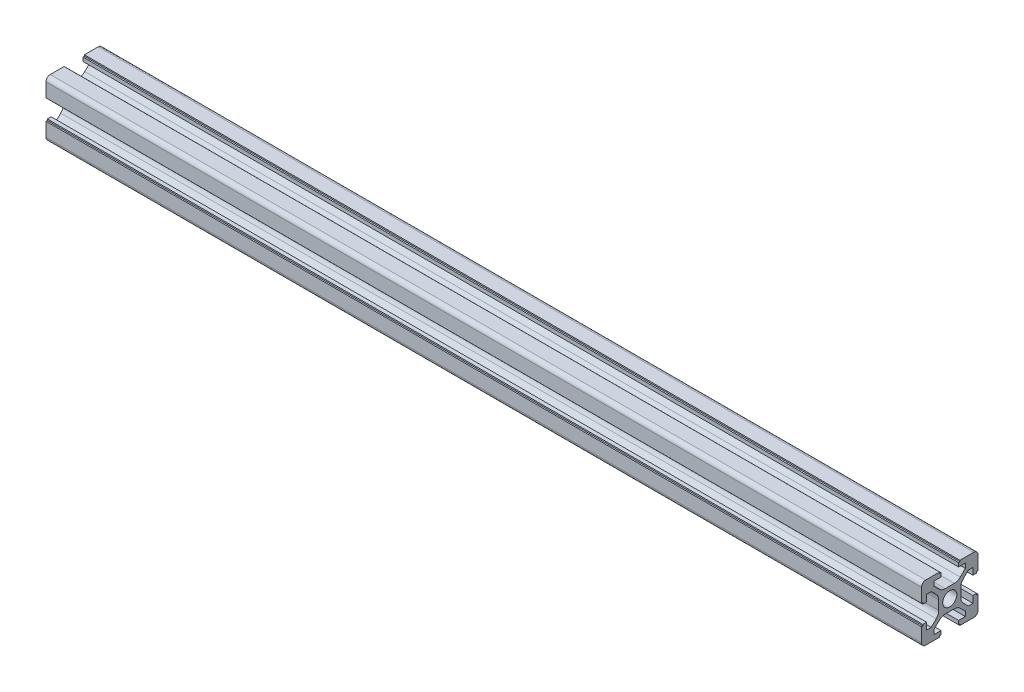
SolidWorks part; units mm, degrees
ref_plane "前视基准面" through (0, 0, 0) normal (0, 0, 1) x (1, 0, 0)
ref_plane "上视基准面" through (0, 0, 0) normal (0, 1, 0) x (1, 0, 0)
ref_plane "右视基准面" through (0, 0, 0) normal (1, 0, 0) x (0, 0, -1)
sketch "草图1" plane through (0, 0, 0) normal (1, 0, 0) x (0, 0, -1)
  line L0 (0, 0) -> (-10, 0) construction
  line L1 (0, 0) -> (0, 10) construction
  line L2 (0, 0) -> (-10, 10) construction
  line L3 (-10, 10) -> (-10, 3.6)
  line L4 (-10, 3.6) -> (-9.531, 3.6)
  line L5 (-9.531, 3.6) -> (-9.531, 3.1)
  line L6 (-9.531, 3.1) -> (-8.2, 3.1)
  line L7 (-8.2, 3.1) -> (-8.2, 5.5)
  line L8 (-8.2, 5.5) -> (-6.5607, 5.5)
  line L9 (-6.5607, 5.5) -> (-3.9, 2.8393)
  line L10 (-3.9, 2.8393) -> (-3.9, 0)
  line L11 (-3.6, 9.531) -> (-3.1, 9.531)
  line L12 (-2.8393, 3.9) -> (0, 3.9)
  line L13 (-5.5, 6.5607) -> (-2.8393, 3.9)
  line L14 (-5.5, 8.2) -> (-5.5, 6.5607)
  line L15 (-3.1, 8.2) -> (-5.5, 8.2)
  line L16 (-3.1, 9.531) -> (-3.1, 8.2)
  line L17 (-3.6, 10) -> (-3.6, 9.531)
  line L18 (-10, 10) -> (-3.6, 10)
  line L19 (0, 0) -> (0, 10) construction
  line L20 (0, 0) -> (10, 0) construction
  line L21 (0, 0) -> (10, 10) construction
  line L22 (10, 10) -> (3.6, 10)
  line L23 (3.6, 10) -> (3.6, 9.531)
  line L24 (3.6, 9.531) -> (3.1, 9.531)
  line L25 (3.1, 9.531) -> (3.1, 8.2)
  line L26 (3.1, 8.2) -> (5.5, 8.2)
  line L27 (5.5, 8.2) -> (5.5, 6.5607)
  line L28 (5.5, 6.5607) -> (2.8393, 3.9)
  line L29 (2.8393, 3.9) -> (0, 3.9)
  line L30 (9.531, 3.6) -> (9.531, 3.1)
  line L31 (3.9, 2.8393) -> (3.9, 0)
  line L32 (6.5607, 5.5) -> (3.9, 2.8393)
  line L33 (8.2, 5.5) -> (6.5607, 5.5)
  line L34 (8.2, 3.1) -> (8.2, 5.5)
  line L35 (9.531, 3.1) -> (8.2, 3.1)
  line L36 (10, 3.6) -> (9.531, 3.6)
  line L37 (10, 10) -> (10, 3.6)
  line L38 (0, 0) -> (10, 0) construction
  line L39 (0, 0) -> (0, -10) construction
  line L40 (0, 0) -> (10, -10) construction
  line L41 (10, -10) -> (10, -3.6)
  line L42 (10, -3.6) -> (9.531, -3.6)
  line L43 (9.531, -3.6) -> (9.531, -3.1)
  line L44 (9.531, -3.1) -> (8.2, -3.1)
  line L45 (8.2, -3.1) -> (8.2, -5.5)
  line L46 (8.2, -5.5) -> (6.5607, -5.5)
  line L47 (6.5607, -5.5) -> (3.9, -2.8393)
  line L48 (3.9, -2.8393) -> (3.9, 0)
  line L49 (3.6, -9.531) -> (3.1, -9.531)
  line L50 (2.8393, -3.9) -> (0, -3.9)
  line L51 (5.5, -6.5607) -> (2.8393, -3.9)
  line L52 (5.5, -8.2) -> (5.5, -6.5607)
  line L53 (3.1, -8.2) -> (5.5, -8.2)
  line L54 (3.1, -9.531) -> (3.1, -8.2)
  line L55 (3.6, -10) -> (3.6, -9.531)
  line L56 (10, -10) -> (3.6, -10)
  line L57 (0, 0) -> (0, -10) construction
  line L58 (0, 0) -> (-10, 0) construction
  line L59 (0, 0) -> (-10, -10) construction
  line L60 (-10, -10) -> (-3.6, -10)
  line L61 (-3.6, -10) -> (-3.6, -9.531)
  line L62 (-3.6, -9.531) -> (-3.1, -9.531)
  line L63 (-3.1, -9.531) -> (-3.1, -8.2)
  line L64 (-3.1, -8.2) -> (-5.5, -8.2)
  line L65 (-5.5, -8.2) -> (-5.5, -6.5607)
  line L66 (-5.5, -6.5607) -> (-2.8393, -3.9)
  line L67 (-2.8393, -3.9) -> (0, -3.9)
  line L68 (-9.531, -3.6) -> (-9.531, -3.1)
  line L69 (-3.9, -2.8393) -> (-3.9, 0)
  line L70 (-6.5607, -5.5) -> (-3.9, -2.8393)
  line L71 (-8.2, -5.5) -> (-6.5607, -5.5)
  line L72 (-8.2, -3.1) -> (-8.2, -5.5)
  line L73 (-9.531, -3.1) -> (-8.2, -3.1)
  line L74 (-10, -3.6) -> (-9.531, -3.6)
  line L75 (-10, -10) -> (-10, -3.6)
  arc A0 (0, 2.5) -> (-2.5, 0) centre (0, 0) ccw
  arc A1 (2.5, 0) -> (0, 2.5) centre (0, 0) ccw
  arc A2 (0, -2.5) -> (2.5, 0) centre (0, 0) ccw
  arc A3 (-2.5, 0) -> (0, -2.5) centre (0, 0) ccw
  point P89 (0, 0)
  dimension "D3" = 5
  dimension "D1" = 10
  dimension "D2" = 10
  dimension "D4" = 10
  dimension "D5" = 1.8
  dimension "D6" = 5.5
  dimension "D7" = 3.1
  dimension "D8" = 3.6
  dimension "D9" = 6.1
  dimension "D10" = 0.75
  dimension "D11" = 4
extrude "凸台-拉伸1" add sketch "草图1" along normal blind 310
fillet "圆角1" radius 1.5 4 edges at (155, -10, -10) (155, -10, 10) (155, 10, -10) (155, 10, 10)
fillet "圆角2" radius 3 8 edges at (155, -3.9, 2.8393) (155, -3.9, -2.8393) (155, -2.8393, -3.9) (155, 2.8393, -3.9) (155, 2.8393, 3.9) (155, -2.8393, 3.9) (155, 3.9, 2.8393) (155, 3.9, -2.8393)
